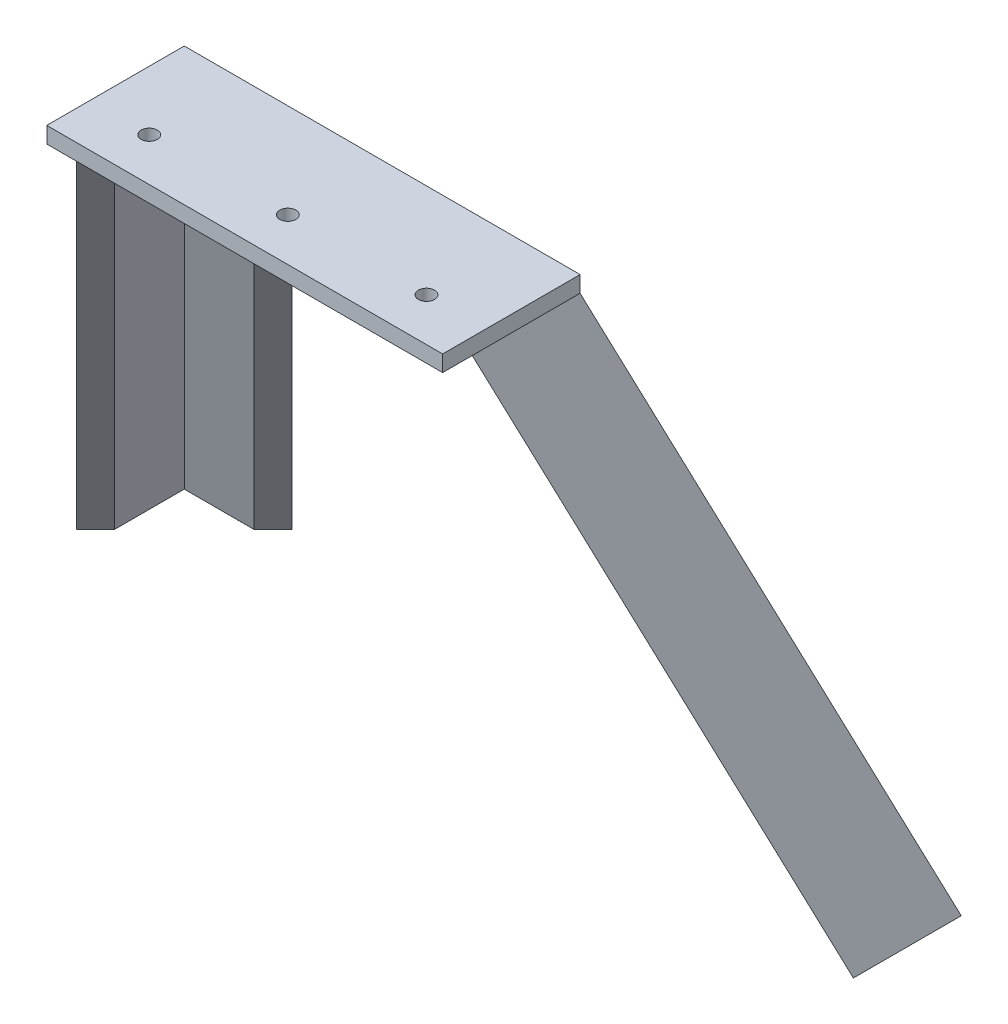
SolidWorks part; units mm, degrees
ref_plane "前视基准面" through (0, 0, 0) normal (0, 0, 1) x (1, 0, 0)
ref_plane "上视基准面" through (0, 0, 0) normal (0, 1, 0) x (1, 0, 0)
ref_plane "右视基准面" through (0, 0, 0) normal (1, 0, 0) x (0, 0, -1)
other "Configuration Table"
ref_plane "基准面2" through (0, 100, 0) normal (0, 1, 0) x (1, 0, 0)
sketch "草图8" plane through (0, 100, 0) normal (0, 1, 0) x (1, 0, 0)
  line L1 (-47.7955, 35.7204) -> (25.6259, 35.7204)
  line L2 (-47.7955, 35.7204) -> (-47.7955, 10.2204)
  line L3 (-47.7955, 10.2204) -> (25.6259, 10.2204)
  line L4 (25.6259, 35.7204) -> (25.6259, 10.2204)
extrude "凸台-拉伸3" add sketch "草图8" along normal blind 3
sketch "草图9" plane through (0, 103, 0) normal (0, 1, 0) x (1, 0, 0)
  circle A0 centre (-36.7955, 18.2204) radius 1.5
  circle A1 centre (14.6259, 18.2204) radius 1.5
  circle A2 centre (-11.0848, 18.2204) radius 1.5
extrude "切除-拉伸2" cut sketch "草图9" against normal blind 3
sketch "草图10" plane through (0, 100, 0) normal (0, 1, 0) x (1, 0, 0)
  line L0 (-47.7955, 35.7204) -> (-27.7955, 35.7204)
  line L1 (25.6259, 35.7204) -> (-47.7955, 35.7204) construction
  line L2 (-47.7955, 35.7204) -> (-47.7955, 15.7204)
  line L3 (-47.7955, 35.7204) -> (-47.7955, 10.2204) construction
  line L4 (-27.7955, 35.7204) -> (-47.7955, 15.7204)
sketch "草图11" plane through (0, 0, 0) normal (0, 1, 0) x (1, 0, 0)
  line L0 (-83.1508, 71.0757) -> (-63.1508, 71.0757)
  line L1 (-63.1508, 71.0757) -> (-83.1508, 51.0757)
  line L2 (-83.1508, 51.0757) -> (-83.1508, 71.0757)
loft "放样2" add profiles "草图10", "草图11"
sketch "草图12" plane through (0, 100, 0) normal (0, 1, 0) x (1, 0, 0)
  line L0 (-31.331, 32.1849) -> (-44.2599, 19.2559)
  line L3 (-44.2599, 32.1849) -> (-31.331, 32.1849)
  line L9 (-44.2599, 32.1849) -> (-44.2599, 19.2559)
sketch "草图13" plane through (0, 0, 0) normal (0, 1, 0) x (1, 0, 0)
  line L1 (-47.7955, 35.7204) -> (-83.1508, 71.0757) construction
  line L3 (-66.6863, 67.5402) -> (-79.6153, 54.6113)
  line L4 (-79.6153, 67.5402) -> (-66.6863, 67.5402)
  line L5 (-79.6153, 67.5402) -> (-79.6153, 54.6113)
loft "切除-放样1" cut profiles "草图12", "草图13"
ref_plane "基准面4" through (-11, 0, 0) normal (1, 0, 0) x (0, 0, -1)
ref_plane "基准面6" through (-11.1, 0, 0) normal (1, 0, 0) x (0, 0, -1)
mirror "镜向3" about plane through (-11.1, 0, 0) normal (1, 0, 0) of "放样2"
mirror "镜向4" about plane through (-11.1, 0, 0) normal (1, 0, 0) of "切除-放样1"
